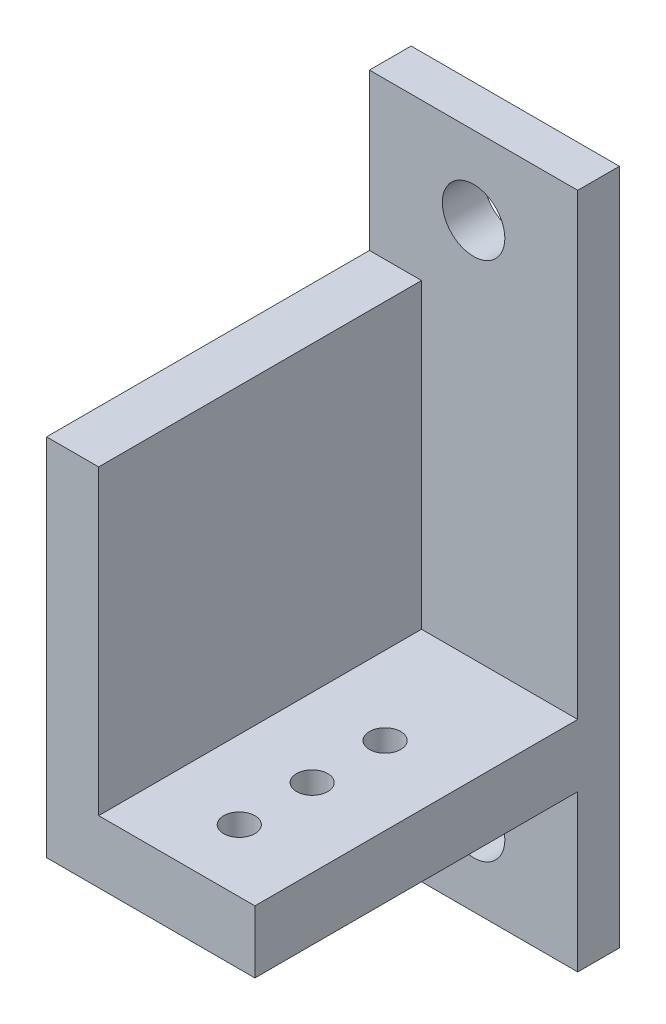
SolidWorks part; units mm, degrees
ref_plane "Front Plane" through (0, 0, 0) normal (0, 0, 1) x (1, 0, 0)
ref_plane "Top Plane" through (0, 0, 0) normal (0, 1, 0) x (1, 0, 0)
ref_plane "Right Plane" through (0, 0, 0) normal (1, 0, 0) x (0, 0, -1)
sketch "Sketch1" plane through (0, 0, 0) normal (0, 0, 1) x (1, 0, 0)
  line L0 (12.369, 15.6457) -> (-2.631, 15.6457)
  line L1 (-7.631, -13.3543) -> (-2.631, -13.3543)
  line L2 (-7.631, -13.3543) -> (-7.631, 21.6457)
  line L3 (-7.631, 21.6457) -> (12.369, 21.6457)
  line L4 (12.369, 15.6457) -> (12.369, 21.6457)
  line L5 (-7.631, -13.3543) -> (12.369, 21.6457) construction
  line L6 (-7.631, 21.6457) -> (0, 0) construction
  line L7 (-2.631, 15.6457) -> (-2.631, -13.3543)
  point P0 (0, 0)
  dimension "D1" = 6
  dimension "D2" = 5
  dimension "D3" = 29
  dimension "D4" = 15
extrude "Boss-Extrude1" add sketch "Sketch1" along normal blind 35
sketch "Sketch2" plane through (-7.631, 0, 0) normal (-1, 0, 0) x (0, 0, 1)
  line L0 (0, 21.6457) -> (4, 21.6457)
  line L1 (35, 21.6457) -> (0, 21.6457) construction
  line L2 (4, 21.6457) -> (4, -13.3543)
  line L3 (35, -13.3543) -> (0, -13.3543) construction
  line L4 (4, -13.3543) -> (0, -13.3543)
  line L5 (0, 21.6457) -> (0, -13.3543)
  dimension "D1" = 4
sketch "Sketch3" plane through (0, 15.6457, 0) normal (0, -1, 0) x (1, 0, 0)
  line L0 (-2.631, 35) -> (12.369, 35) construction
  line L1 (12.369, 35) -> (12.369, 0) construction
  circle A0 centre (4.869, 29) radius 1.5
  dimension "D1" = 3
  dimension "D2" = 6
  dimension "D3" = 7.5
extrude "Cut-Extrude1" cut sketch "Sketch3" against normal blind 15
pattern_linear "LPattern1" count 3 spacing 7 along (0, 0, -1) of "Cut-Extrude1"
sketch "Sketch6" plane through (0, -13.3543, 0) normal (0, -1, 0) x (1, 0, 0)
  line L4 (-2.631, 35) -> (-2.631, 0)
  line L5 (-2.631, 0) -> (12.369, 0)
  line L6 (12.369, 0) -> (12.369, 35)
  line L7 (12.369, 35) -> (-2.631, 35)
  line L8 (-2.631, 35) -> (-2.631, 0)
  line L9 (-2.631, 0) -> (12.369, 0)
  line L10 (12.369, 0) -> (12.369, 35)
  line L11 (12.369, 35) -> (-2.631, 35)
  circle A0 centre (4.869, 15) radius 1.5 construction
  circle A1 centre (4.869, 29) radius 1.5 construction
  circle A2 centre (4.869, 22) radius 1.5 construction
  circle A3 centre (4.869, 15) radius 1.5
  circle A4 centre (4.869, 29) radius 1.5
  circle A5 centre (4.869, 22) radius 1.5
  dimension "D1" = 0
extrude "Boss-Extrude4" add sketch "Sketch6" against normal blind 6
sketch "Sketch7" plane through (0, 15.6457, 0) normal (0, -1, 0) x (1, 0, 0)
  line L4 (-2.631, 35) -> (-2.631, 0)
  line L5 (-2.631, 0) -> (12.369, 0)
  line L6 (12.369, 0) -> (12.369, 35)
  line L7 (12.369, 35) -> (-2.631, 35)
  line L8 (-2.631, 35) -> (-2.631, 0)
  line L9 (-2.631, 0) -> (12.369, 0)
  line L10 (12.369, 0) -> (12.369, 35)
  line L11 (12.369, 35) -> (-2.631, 35)
  dimension "D1" = 0
extrude "Cut-Extrude2" cut sketch "Sketch7" against normal blind 8
extrude "Boss-Extrude5" add sketch "Sketch2" against normal up to surface (20 mm away) contours L2 L4 L5 L0 up to face at (12.369, -10.3543, 17.5)
sketch "Sketch9" plane through (0, 21.6457, 0) normal (0, 1, 0) x (1, 0, 0)
  line L0 (-2.631, -4) -> (-7.631, -4)
  line L6 (12.369, 0) -> (-7.631, 0)
  line L7 (-7.631, 0) -> (-7.631, -35)
  line L8 (-7.631, -35) -> (-2.631, -35)
  line L9 (-2.631, -35) -> (-2.631, -4)
  line L10 (-2.631, -4) -> (12.369, -4)
  line L11 (12.369, -4) -> (12.369, 0)
  line L12 (12.369, 0) -> (-7.631, 0)
  line L13 (-7.631, 0) -> (-7.631, -4)
  line L16 (-2.631, -4) -> (12.369, -4)
  line L17 (12.369, -4) -> (12.369, 0)
  dimension "D1" = 0
extrude "Boss-Extrude6" add sketch "Sketch9" along normal blind 15
sketch "Sketch10" plane through (0, -13.3543, 0) normal (0, -1, 0) x (1, 0, 0)
  line L4 (12.369, 0) -> (12.369, 4)
  line L5 (-7.631, 0) -> (12.369, 0)
  line L6 (-7.631, 4) -> (-7.631, 0)
  line L7 (12.369, 4) -> (-7.631, 4)
  line L8 (12.369, 0) -> (12.369, 4)
  line L9 (-7.631, 0) -> (12.369, 0)
  line L10 (-7.631, 4) -> (-7.631, 0)
  line L11 (12.369, 4) -> (-7.631, 4)
  dimension "D1" = 0
extrude "Boss-Extrude7" add sketch "Sketch10" along normal blind 15
sketch "Sketch11" plane through (0, 0, 4) normal (0, 0, 1) x (1, 0, 0)
  line L0 (2.369, -28.3543) -> (2.369, 36.6457) construction
  line L1 (12.369, -28.3543) -> (-7.631, -28.3543) construction
  line L2 (-7.631, 36.6457) -> (12.369, 36.6457) construction
  circle A0 centre (2.369, -20.8543) radius 3
  circle A1 centre (2.369, 29.1457) radius 3
  point P9 (0.9301, -26.2763)
  point P10 (0, 0)
  dimension "D1" = 6
  dimension "D2" = 6
  dimension "D3" = 50
  dimension "D4" = 7.5
extrude "Cut-Extrude3" cut sketch "Sketch11" against normal blind 15
